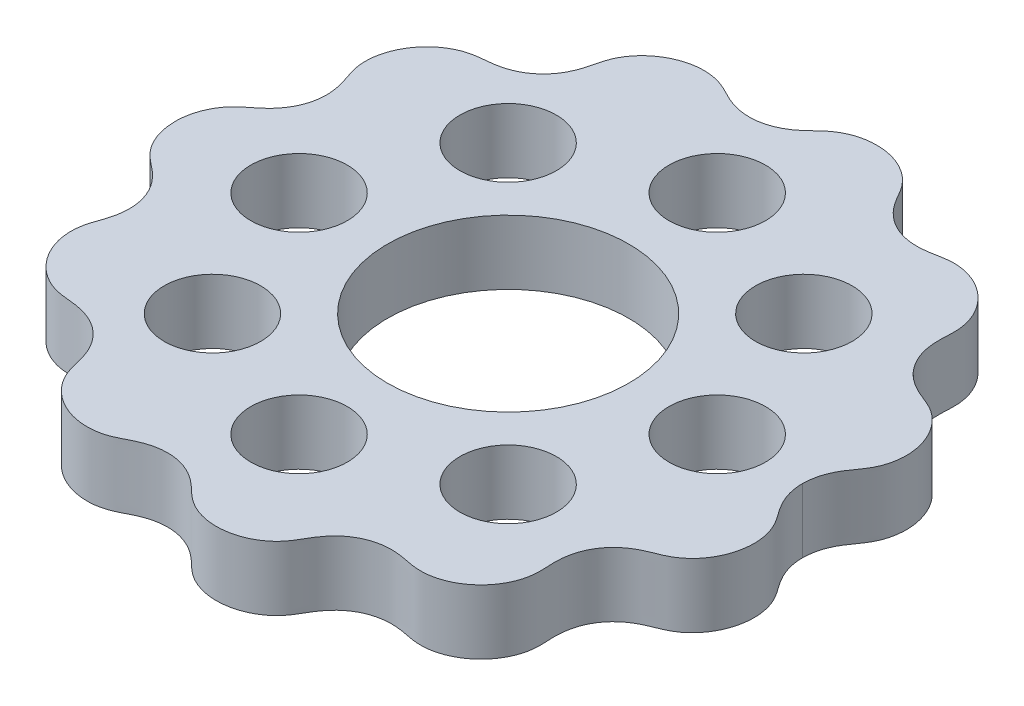
SolidWorks part; units mm, degrees
ref_plane "Front Plane" through (0, 0, 0) normal (0, 0, 1) x (1, 0, 0)
ref_plane "Top Plane" through (0, 0, 0) normal (0, 1, 0) x (1, 0, 0)
ref_plane "Right Plane" through (0, 0, 0) normal (1, 0, 0) x (0, 0, -1)
sketch "Sketch3" plane through (0, 0, 0) normal (0, 1, 0) x (1, 0, 0)
  line L0 (-30.6051, 0) -> (34.7487, 0) construction
  line L1 (0, 0) -> (0, 29.2445) construction
  spline S0 degree 4 poles (11.6189, 16.5432) (11.8178, 16.5149) (12.2108, 16.4276) (12.9492, 16.1436) (13.746, 15.5555) (14.3617, 14.7904) (14.7236, 13.9501) (14.8612, 13.2918) (14.865, 12.6715) (14.8197, 12.1053) (14.83, 11.5815) (14.8956, 11.1092) (15.007, 10.6932) (15.1452, 10.3349) (15.3154, 10.0076) (15.511, 9.7126) (15.7246, 9.4508) (15.9525, 9.2201) (16.1975, 9.0122) (16.4653, 8.8248) (16.7029, 8.6844) (16.9312, 8.5703) (17.1246, 8.4809) (17.3959, 8.3693) (17.5318, 8.3168) (17.8356, 8.1923) (18.031, 8.0988) (18.2545, 7.9769) (18.4535, 7.8462) (18.6983, 7.6613) (18.9517, 7.427) (19.209, 7.1339) (19.4525, 6.7789) (19.6486, 6.416) (19.8087, 6.0265) (19.9293, 5.6134) (20.0053, 5.1807) (20.0322, 4.7331) (20.0052, 4.2575) (19.9105, 3.7618) (19.734, 3.2584) (19.4598, 2.7684) (19.1286, 2.3294) (18.8254, 1.8814) (18.5806, 1.4078) (18.4064, 0.9137) (18.2839, 0.2821) (18.2883, -0.4839) (18.4665, -1.1796) (18.761, -1.77) (19.0269, -2.1778) (19.2109, -2.4357) (19.3957, -2.6929) (19.5656, -2.9607) (19.7479, -3.3127) (19.9386, -3.8341) (20.0574, -4.5402) (20.0084, -5.4053) (19.7399, -6.2999) (19.3164, -7.0355) (18.8045, -7.5977) (18.2523, -8.0019) (17.7028, -8.2583) (17.046, -8.4959) (16.3381, -8.8646) (15.6539, -9.4505) (15.1112, -10.2886) (14.8757, -11.08) (14.8227, -11.7251) (14.8331, -12.2747) (14.8653, -12.7277) (14.8627, -13.2601) (14.7284, -13.933) (14.4312, -14.6359) (13.9398, -15.3293) (13.2393, -15.9473) (12.4754, -16.3531) (11.7867, -16.5408) (11.2352, -16.5867) (10.8405, -16.5694) (10.5271, -16.5278) (10.2173, -16.4674) (9.9074, -16.4068) (9.4278, -16.3326) (8.7706, -16.3058) (7.9522, -16.4462) (7.0575, -16.8866) (6.3973, -17.4923) (5.9486, -18.142) (5.6247, -18.753) (5.2858, -19.2492) (4.8047, -19.7257) (4.176, -20.14) (3.4024, -20.4398) (2.5087, -20.57) (1.6927, -20.5039) (0.9916, -20.296) (0.4189, -19.998) (-0.0273, -19.6575) (-0.4146, -19.2674) (-0.8145, -18.9035) (-1.248, -18.5935) (-1.7119, -18.3505) (-2.3194, -18.1387) (-3.0782, -18.0333) (-3.7924, -18.11) (-4.4191, -18.3171) (-4.861, -18.5221) (-5.1425, -18.6675) (-5.4235, -18.8139) (-5.7127, -18.9442) (-6.0871, -19.0749) (-6.6306, -19.1899) (-7.3467, -19.2073) (-8.1962, -19.036) (-9.0436, -18.6432) (-9.7116, -18.1198) (-10.1953, -17.5335) (-10.5171, -16.93) (-10.6931, -16.3498) (-10.8346, -15.6663) (-11.0981, -14.9129) (-11.5802, -14.1521) (-12.3327, -13.4935) (-13.154, -13.1159) (-13.9425, -12.956) (-14.6452, -12.9123) (-15.2508, -12.8226) (-15.8975, -12.5902) (-16.5474, -12.1958) (-17.16, -11.6117) (-17.6691, -10.8344) (-17.9616, -10.0228) (-18.0497, -9.3149) (-18.017, -8.7626) (-17.9441, -8.3745) (-17.8585, -8.0703) (-17.7548, -7.7723) (-17.6507, -7.4743) (-17.5088, -7.0104) (-17.3883, -6.3641) (-17.4099, -5.5341) (-17.7175, -4.5856) (-18.2225, -3.8453) (-18.8015, -3.308) (-19.3605, -2.9003) (-19.8039, -2.4944) (-20.2076, -1.9504) (-20.5288, -1.269) (-20.7158, -0.4605) (-20.7178, 0.4427) (-20.5366, 1.2408) (-20.2316, 1.9051) (-19.8556, 2.4296) (-19.4556, 2.8229) (-19.0146, 3.1507) (-18.5974, 3.4944) (-18.2288, 3.8789) (-17.9219, 4.3031) (-17.6253, 4.8739) (-17.4121, 5.6098) (-17.3857, 6.3278) (-17.501, 6.9779) (-17.6409, 7.4447) (-17.7447, 7.7443) (-17.8497, 8.0433) (-17.9378, 8.3482) (-18.0142, 8.7375) (-18.051, 9.292) (-17.9667, 10.0036) (-17.6765, 10.8204) (-17.1675, 11.6035) (-16.5546, 12.1903) (-15.906, 12.5859) (-15.2632, 12.8188) (-14.6642, 12.9109) (-13.9676, 12.9536) (-13.185, 13.1065) (-12.3627, 13.4746) (-11.6037, 14.1249) (-11.1111, 14.8837) (-10.8676, 15.5695) (-10.7424, 16.1072) (-10.6331, 16.5515) (-10.4857, 16.9859) (-10.2015, 17.5258) (-9.7176, 18.1133) (-9.0531, 18.6371) (-8.2109, 19.0306) (-7.3665, 19.205) (-6.6533, 19.1918) (-6.1116, 19.0813) (-5.7378, 18.9541) (-5.4489, 18.8264) (-5.1688, 18.6814) (-4.8888, 18.536) (-4.4501, 18.3294) (-3.8279, 18.1177) (-3.0036, 18.0202) (-2.0208, 18.1887) (-1.2156, 18.5825) (-0.6007, 19.0789) (-0.1174, 19.5743) (0.3474, 19.956) (0.9434, 20.2787) (1.6637, 20.5001) (2.4907, 20.5705) (3.385, 20.4443) (4.1492, 20.1518) (4.7633, 19.7558) (5.229, 19.3095) (5.5616, 18.8581) (5.8234, 18.3752) (6.1038, 17.9134) (6.4315, 17.4937) (6.8071, 17.1293) (7.2217, 16.8315) (7.6634, 16.6034) (8.1203, 16.4444) (8.5815, 16.3511) (9.0507, 16.319) (9.4616, 16.3412) (9.8101, 16.3903) (10.0986, 16.4439) (10.3282, 16.4895) (10.5311, 16.526) (10.7049, 16.5505) (10.8484, 16.5653) (10.9716, 16.5733) (11.0921, 16.577) (11.1677, 16.5774) (11.2594, 16.5751) (11.3499, 16.5709) (11.4367, 16.5647) (11.5194, 16.5564) (11.6217, 16.5435) (11.7453, 16.524) (11.889, 16.4956) (12.0913, 16.4453) (12.3305, 16.3702) (12.602, 16.2618) (12.9005, 16.1114) (13.1849, 15.9359) (13.4773, 15.7195) (13.7698, 15.4569) (14.0541, 15.1433) (14.3167, 14.7752) (14.5534, 14.3454) (14.7409, 13.8521) (14.8591, 13.2967) (14.8673, 12.6928) (14.8104, 11.9996) (14.8464, 11.2056) (15.0918, 10.3263) (15.5701, 9.57) (16.1316, 9.0373) (16.5735, 8.7549) (16.8048, 8.6327) (16.9225, 8.5759) knots 0 0 0 0 0 0.005432 0.010864 0.021228 0.026411 0.031594 0.035438 0.039283 0.043127 0.046971 0.049563 0.052156 0.054748 0.057341 0.059524 0.061707 0.06389 0.066073 0.068256 0.070439 0.07153 0.072622 0.074805 0.076449 0.078093 0.079737 0.081382 0.083026 0.08467 0.087958 0.090741 0.093524 0.096307 0.09909 0.102115 0.105141 0.108166 0.111192 0.114971 0.11875 0.122529 0.126307 0.129839 0.133371 0.136903 0.140435 0.147176 0.153918 0.15606 0.158202 0.160344 0.162486 0.164628 0.16677 0.171054 0.177448 0.183843 0.189974 0.196106 0.20019 0.204275 0.20836 0.212445 0.219092 0.225739 0.23241 0.239081 0.24113 0.243178 0.247276 0.251373 0.255471 0.261622 0.267773 0.274148 0.280522 0.284792 0.286927 0.289062 0.291197 0.293332 0.295467 0.297602 0.304323 0.311044 0.317625 0.324205 0.32825 0.332295 0.33634 0.340384 0.346455 0.352526 0.358575 0.364624 0.368401 0.372178 0.375955 0.379732 0.383263 0.386793 0.390324 0.393854 0.400599 0.407343 0.409486 0.411628 0.413771 0.415914 0.418057 0.4202 0.424485 0.430883 0.43728 0.443409 0.449537 0.453621 0.457704 0.461787 0.465871 0.472515 0.479159 0.485846 0.492533 0.496656 0.50078 0.504903 0.509026 0.515118 0.52121 0.527582 0.533954 0.538222 0.540357 0.542491 0.544625 0.546759 0.548893 0.551027 0.557745 0.564464 0.571047 0.57763 0.581676 0.585723 0.589769 0.593816 0.59989 0.605963 0.612009 0.618055 0.621831 0.625606 0.629382 0.633157 0.636687 0.640216 0.643745 0.647274 0.654021 0.660768 0.662911 0.665055 0.667199 0.669342 0.671486 0.67363 0.677917 0.684317 0.690717 0.696843 0.702969 0.707051 0.711133 0.715214 0.719296 0.725937 0.732578 0.739268 0.745958 0.750083 0.752145 0.754208 0.758333 0.762458 0.768552 0.774647 0.781016 0.787386 0.791652 0.793786 0.795919 0.798052 0.800186 0.802319 0.804452 0.811168 0.817883 0.824469 0.831054 0.835103 0.839151 0.843199 0.847248 0.853324 0.8594 0.865444 0.871487 0.875261 0.879035 0.882809 0.886583 0.89011 0.893638 0.897166 0.900694 0.903866 0.907039 0.910211 0.913384 0.916556 0.918143 0.919729 0.921315 0.922901 0.923694 0.924488 0.925281 0.926074 0.926638 0.927203 0.927767 0.928331 0.928896 0.92946 0.930589 0.931717 0.932846 0.935103 0.937361 0.939618 0.941875 0.944133 0.947186 0.95024 0.953293 0.956347 0.960414 0.964482 0.968549 0.972617 0.979237 0.985858 0.992929 0.996465 1 1 1 1 1 construction
  spline S1 degree 4 poles (18.3, 0) (18.3, -0.215) (18.3388, -0.6792) (18.4818, -1.2103) (18.761, -1.77) (19.0269, -2.1778) (19.2109, -2.4357) (19.3957, -2.6929) (19.5656, -2.9607) (19.7479, -3.3127) (19.9386, -3.8341) (20.0574, -4.5402) (20.0084, -5.4053) (19.7399, -6.2999) (19.3164, -7.0355) (18.8045, -7.5977) (18.2523, -8.0019) (17.7028, -8.2583) (17.046, -8.4959) (16.3381, -8.8646) (15.6539, -9.4505) (15.1112, -10.2886) (14.8757, -11.08) (14.8227, -11.7251) (14.8331, -12.2747) (14.8653, -12.7277) (14.8627, -13.2601) (14.7284, -13.933) (14.4312, -14.6359) (13.9398, -15.3293) (13.2393, -15.9473) (12.4754, -16.3531) (11.7867, -16.5408) (11.2352, -16.5867) (10.8405, -16.5694) (10.5271, -16.5278) (10.2173, -16.4674) (9.9074, -16.4068) (9.4278, -16.3326) (8.7706, -16.3058) (7.9522, -16.4462) (7.0575, -16.8866) (6.3973, -17.4923) (5.9486, -18.142) (5.6247, -18.753) (5.2858, -19.2492) (4.8047, -19.7257) (4.176, -20.14) (3.4024, -20.4398) (2.5087, -20.57) (1.6927, -20.5039) (0.9916, -20.296) (0.4189, -19.998) (-0.0273, -19.6575) (-0.4146, -19.2674) (-0.8145, -18.9035) (-1.248, -18.5935) (-1.7119, -18.3505) (-2.3194, -18.1387) (-3.0782, -18.0333) (-3.7924, -18.11) (-4.4191, -18.3171) (-4.861, -18.5221) (-5.1425, -18.6675) (-5.4235, -18.8139) (-5.7127, -18.9442) (-6.0871, -19.0749) (-6.6306, -19.1899) (-7.3467, -19.2073) (-8.1962, -19.036) (-9.0436, -18.6432) (-9.7116, -18.1198) (-10.1953, -17.5335) (-10.5171, -16.93) (-10.6931, -16.3498) (-10.8346, -15.6663) (-11.0981, -14.9129) (-11.5802, -14.1521) (-12.3327, -13.4935) (-13.154, -13.1159) (-13.9425, -12.956) (-14.6452, -12.9123) (-15.2508, -12.8226) (-15.8975, -12.5902) (-16.5474, -12.1958) (-17.16, -11.6117) (-17.6691, -10.8344) (-17.9616, -10.0228) (-18.0497, -9.3149) (-18.017, -8.7626) (-17.9441, -8.3745) (-17.8585, -8.0703) (-17.7548, -7.7723) (-17.6507, -7.4743) (-17.5088, -7.0104) (-17.3883, -6.3641) (-17.4099, -5.5341) (-17.7175, -4.5856) (-18.2225, -3.8453) (-18.8015, -3.308) (-19.3605, -2.9003) (-19.8039, -2.4944) (-20.2076, -1.9504) (-20.5295, -1.2674) (-20.6657, -0.677) (-20.7, -0.2262) (-20.7, 0) knots 0.14136 0.14136 0.14136 0.14136 0.14136 0.147176 0.153918 0.15606 0.158202 0.160344 0.162486 0.164628 0.16677 0.171054 0.177448 0.183843 0.189974 0.196106 0.20019 0.204275 0.20836 0.212445 0.219092 0.225739 0.23241 0.239081 0.24113 0.243178 0.247276 0.251373 0.255471 0.261622 0.267773 0.274148 0.280522 0.284792 0.286927 0.289062 0.291197 0.293332 0.295467 0.297602 0.304323 0.311044 0.317625 0.324205 0.32825 0.332295 0.33634 0.340384 0.346455 0.352526 0.358575 0.364624 0.368401 0.372178 0.375955 0.379732 0.383263 0.386793 0.390324 0.393854 0.400599 0.407343 0.409486 0.411628 0.413771 0.415914 0.418057 0.4202 0.424485 0.430883 0.43728 0.443409 0.449537 0.453621 0.457704 0.461787 0.465871 0.472515 0.479159 0.485846 0.492533 0.496656 0.50078 0.504903 0.509026 0.515118 0.52121 0.527582 0.533954 0.538222 0.540357 0.542491 0.544625 0.546759 0.548893 0.551027 0.557745 0.564464 0.571047 0.57763 0.581676 0.585723 0.589769 0.593816 0.59989 0.60601 0.60601 0.60601 0.60601 0.60601
  spline S2 degree 4 poles (18.3, 0) (18.3, 0.215) (18.3388, 0.6792) (18.4818, 1.2103) (18.761, 1.77) (19.0269, 2.1778) (19.2109, 2.4357) (19.3957, 2.6929) (19.5656, 2.9607) (19.7479, 3.3127) (19.9386, 3.8341) (20.0574, 4.5402) (20.0084, 5.4053) (19.7399, 6.2999) (19.3164, 7.0355) (18.8045, 7.5977) (18.2523, 8.0019) (17.7028, 8.2583) (17.046, 8.4959) (16.3381, 8.8646) (15.6539, 9.4505) (15.1112, 10.2886) (14.8757, 11.08) (14.8227, 11.7251) (14.8331, 12.2747) (14.8653, 12.7277) (14.8627, 13.2601) (14.7284, 13.933) (14.4312, 14.6359) (13.9398, 15.3293) (13.2393, 15.9473) (12.4754, 16.3531) (11.7867, 16.5408) (11.2352, 16.5867) (10.8405, 16.5694) (10.5271, 16.5278) (10.2173, 16.4674) (9.9074, 16.4068) (9.4278, 16.3326) (8.7706, 16.3058) (7.9522, 16.4462) (7.0575, 16.8866) (6.3973, 17.4923) (5.9486, 18.142) (5.6247, 18.753) (5.2858, 19.2492) (4.8047, 19.7257) (4.176, 20.14) (3.4024, 20.4398) (2.5087, 20.57) (1.6927, 20.5039) (0.9916, 20.296) (0.4189, 19.998) (-0.0273, 19.6575) (-0.4146, 19.2674) (-0.8145, 18.9035) (-1.248, 18.5935) (-1.7119, 18.3505) (-2.3194, 18.1387) (-3.0782, 18.0333) (-3.7924, 18.11) (-4.4191, 18.3171) (-4.861, 18.5221) (-5.1425, 18.6675) (-5.4235, 18.8139) (-5.7127, 18.9442) (-6.0871, 19.0749) (-6.6306, 19.1899) (-7.3467, 19.2073) (-8.1962, 19.036) (-9.0436, 18.6432) (-9.7116, 18.1198) (-10.1953, 17.5335) (-10.5171, 16.93) (-10.6931, 16.3498) (-10.8346, 15.6663) (-11.0981, 14.9129) (-11.5802, 14.1521) (-12.3327, 13.4935) (-13.154, 13.1159) (-13.9425, 12.956) (-14.6452, 12.9123) (-15.2508, 12.8226) (-15.8975, 12.5902) (-16.5474, 12.1958) (-17.16, 11.6117) (-17.6691, 10.8344) (-17.9616, 10.0228) (-18.0497, 9.3149) (-18.017, 8.7626) (-17.9441, 8.3745) (-17.8585, 8.0703) (-17.7548, 7.7723) (-17.6507, 7.4743) (-17.5088, 7.0104) (-17.3883, 6.3641) (-17.4099, 5.5341) (-17.7175, 4.5856) (-18.2225, 3.8453) (-18.8015, 3.308) (-19.3605, 2.9003) (-19.8039, 2.4944) (-20.2076, 1.9504) (-20.5295, 1.2674) (-20.6657, 0.677) (-20.7, 0.2262) (-20.7, 0) knots 0.14136 0.14136 0.14136 0.14136 0.14136 0.147176 0.153918 0.15606 0.158202 0.160344 0.162486 0.164628 0.16677 0.171054 0.177448 0.183843 0.189974 0.196106 0.20019 0.204275 0.20836 0.212445 0.219092 0.225739 0.23241 0.239081 0.24113 0.243178 0.247276 0.251373 0.255471 0.261622 0.267773 0.274148 0.280522 0.284792 0.286927 0.289062 0.291197 0.293332 0.295467 0.297602 0.304323 0.311044 0.317625 0.324205 0.32825 0.332295 0.33634 0.340384 0.346455 0.352526 0.358575 0.364624 0.368401 0.372178 0.375955 0.379732 0.383263 0.386793 0.390324 0.393854 0.400599 0.407343 0.409486 0.411628 0.413771 0.415914 0.418057 0.4202 0.424485 0.430883 0.43728 0.443409 0.449537 0.453621 0.457704 0.461787 0.465871 0.472515 0.479159 0.485846 0.492533 0.496656 0.50078 0.504903 0.509026 0.515118 0.52121 0.527582 0.533954 0.538222 0.540357 0.542491 0.544625 0.546759 0.548893 0.551027 0.557745 0.564464 0.571047 0.57763 0.581676 0.585723 0.589769 0.593816 0.59989 0.60601 0.60601 0.60601 0.60601 0.60601
sketch "Sketch4" plane through (0, 0, 0) normal (0, 1, 0) x (1, 0, 0)
  line L0 (-200030.6051, 0) -> (200034.7487, 0) construction
  circle A0 centre (0, 0) radius 7.5
  circle A1 centre (0, 0) radius 13 construction
  circle A2 centre (-13, 0) radius 3
  circle A3 centre (-9.1924, 9.1924) radius 3
  circle A4 centre (0, 13) radius 3
  circle A5 centre (9.1924, 9.1924) radius 3
  circle A6 centre (13, 0) radius 3
  circle A7 centre (9.1924, -9.1924) radius 3
  circle A8 centre (0, -13) radius 3
  circle A9 centre (-9.1924, -9.1924) radius 3
  point P8 (0, 0)
  point P9 (15.4334, -4.2634)
  point P24 (0, 0)
  point P25 (0, 0)
  dimension "D2" = 15
  dimension "D1" = 6
  dimension "D3" = 26
  dimension "D4" = 8
sketch "Sketch5" plane through (0, 0, 0) normal (0, 1, 0) x (1, 0, 0)
  circle A0 centre (0, 0) radius 7.5 construction
  circle A1 centre (-9.1924, -9.1924) radius 3 construction
  circle A2 centre (0, -13) radius 3 construction
  circle A3 centre (9.1924, -9.1924) radius 3 construction
  circle A4 centre (13, 0) radius 3 construction
  circle A5 centre (9.1924, 9.1924) radius 3 construction
  circle A6 centre (0, 13) radius 3 construction
  circle A7 centre (-9.1924, 9.1924) radius 3 construction
  circle A8 centre (-13, 0) radius 3 construction
  circle A9 centre (0, 0) radius 7.5
  circle A10 centre (-9.1924, -9.1924) radius 3
  circle A11 centre (0, -13) radius 3
  circle A12 centre (9.1924, -9.1924) radius 3
  circle A13 centre (13, 0) radius 3
  circle A14 centre (9.1924, 9.1924) radius 3
  circle A15 centre (0, 13) radius 3
  circle A16 centre (-9.1924, 9.1924) radius 3
  circle A17 centre (-13, 0) radius 3
  spline S0 degree 4 poles (-2748.9777, 1148.302) (182.2582, 110.6656) (41.0051, -28.4684) (14.4609, -6.8501) (18.761, 1.77) (19.0269, 2.1778) (19.2109, 2.4357) (19.3957, 2.6929) (19.5656, 2.9607) (19.7479, 3.3127) (19.9386, 3.8341) (20.0574, 4.5402) (20.0084, 5.4053) (19.7399, 6.2999) (19.3164, 7.0355) (18.8045, 7.5977) (18.2523, 8.0019) (17.7028, 8.2583) (17.046, 8.4959) (16.3381, 8.8646) (15.6539, 9.4505) (15.1112, 10.2886) (14.8757, 11.08) (14.8227, 11.7251) (14.8331, 12.2747) (14.8653, 12.7277) (14.8627, 13.2601) (14.7284, 13.933) (14.4312, 14.6359) (13.9398, 15.3293) (13.2393, 15.9473) (12.4754, 16.3531) (11.7867, 16.5408) (11.2352, 16.5867) (10.8405, 16.5694) (10.5271, 16.5278) (10.2173, 16.4674) (9.9074, 16.4068) (9.4278, 16.3326) (8.7706, 16.3058) (7.9522, 16.4462) (7.0575, 16.8866) (6.3973, 17.4923) (5.9486, 18.142) (5.6247, 18.753) (5.2858, 19.2492) (4.8047, 19.7257) (4.176, 20.14) (3.4024, 20.4398) (2.5087, 20.57) (1.6927, 20.5039) (0.9916, 20.296) (0.4189, 19.998) (-0.0273, 19.6575) (-0.4146, 19.2674) (-0.8145, 18.9035) (-1.248, 18.5935) (-1.7119, 18.3505) (-2.3194, 18.1387) (-3.0782, 18.0333) (-3.7924, 18.11) (-4.4191, 18.3171) (-4.861, 18.5221) (-5.1425, 18.6675) (-5.4235, 18.8139) (-5.7127, 18.9442) (-6.0871, 19.0749) (-6.6306, 19.1899) (-7.3467, 19.2073) (-8.1962, 19.036) (-9.0436, 18.6432) (-9.7116, 18.1198) (-10.1953, 17.5335) (-10.5171, 16.93) (-10.6931, 16.3498) (-10.8346, 15.6663) (-11.0981, 14.9129) (-11.5802, 14.1521) (-12.3327, 13.4935) (-13.154, 13.1159) (-13.9425, 12.956) (-14.6452, 12.9123) (-15.2508, 12.8226) (-15.8975, 12.5902) (-16.5474, 12.1958) (-17.16, 11.6117) (-17.6691, 10.8344) (-17.9616, 10.0228) (-18.0497, 9.3149) (-18.017, 8.7626) (-17.9441, 8.3745) (-17.8585, 8.0703) (-17.7548, 7.7723) (-17.6507, 7.4743) (-17.5088, 7.0104) (-17.3883, 6.3641) (-17.4099, 5.5341) (-17.7175, 4.5856) (-18.2225, 3.8453) (-18.8015, 3.308) (-19.3605, 2.9003) (-19.8039, 2.4944) (-20.2076, 1.9504) (-26.3458, -11.073) (35.0631, -48.2959) (149.4782, 410.1171) (1411.5598, -2615.9413) knots -0.101211 -0.101211 -0.101211 -0.101211 -0.101211 0.147176 0.153918 0.15606 0.158202 0.160344 0.162486 0.164628 0.16677 0.171054 0.177448 0.183843 0.189974 0.196106 0.20019 0.204275 0.20836 0.212445 0.219092 0.225739 0.23241 0.239081 0.24113 0.243178 0.247276 0.251373 0.255471 0.261622 0.267773 0.274148 0.280522 0.284792 0.286927 0.289062 0.291197 0.293332 0.295467 0.297602 0.304323 0.311044 0.317625 0.324205 0.32825 0.332295 0.33634 0.340384 0.346455 0.352526 0.358575 0.364624 0.368401 0.372178 0.375955 0.379732 0.383263 0.386793 0.390324 0.393854 0.400599 0.407343 0.409486 0.411628 0.413771 0.415914 0.418057 0.4202 0.424485 0.430883 0.43728 0.443409 0.449537 0.453621 0.457704 0.461787 0.465871 0.472515 0.479159 0.485846 0.492533 0.496656 0.50078 0.504903 0.509026 0.515118 0.52121 0.527582 0.533954 0.538222 0.540357 0.542491 0.544625 0.546759 0.548893 0.551027 0.557745 0.564464 0.571047 0.57763 0.581676 0.585723 0.589769 0.593816 0.59989 0.972598 0.972598 0.972598 0.972598 0.972598 only from (18.3, 0) to (-20.7, 0) construction
  spline S1 degree 4 poles (-2748.9777, -1148.302) (182.2582, -110.6656) (41.0051, 28.4684) (14.4609, 6.8501) (18.761, -1.77) (19.0269, -2.1778) (19.2109, -2.4357) (19.3957, -2.6929) (19.5656, -2.9607) (19.7479, -3.3127) (19.9386, -3.8341) (20.0574, -4.5402) (20.0084, -5.4053) (19.7399, -6.2999) (19.3164, -7.0355) (18.8045, -7.5977) (18.2523, -8.0019) (17.7028, -8.2583) (17.046, -8.4959) (16.3381, -8.8646) (15.6539, -9.4505) (15.1112, -10.2886) (14.8757, -11.08) (14.8227, -11.7251) (14.8331, -12.2747) (14.8653, -12.7277) (14.8627, -13.2601) (14.7284, -13.933) (14.4312, -14.6359) (13.9398, -15.3293) (13.2393, -15.9473) (12.4754, -16.3531) (11.7867, -16.5408) (11.2352, -16.5867) (10.8405, -16.5694) (10.5271, -16.5278) (10.2173, -16.4674) (9.9074, -16.4068) (9.4278, -16.3326) (8.7706, -16.3058) (7.9522, -16.4462) (7.0575, -16.8866) (6.3973, -17.4923) (5.9486, -18.142) (5.6247, -18.753) (5.2858, -19.2492) (4.8047, -19.7257) (4.176, -20.14) (3.4024, -20.4398) (2.5087, -20.57) (1.6927, -20.5039) (0.9916, -20.296) (0.4189, -19.998) (-0.0273, -19.6575) (-0.4146, -19.2674) (-0.8145, -18.9035) (-1.248, -18.5935) (-1.7119, -18.3505) (-2.3194, -18.1387) (-3.0782, -18.0333) (-3.7924, -18.11) (-4.4191, -18.3171) (-4.861, -18.5221) (-5.1425, -18.6675) (-5.4235, -18.8139) (-5.7127, -18.9442) (-6.0871, -19.0749) (-6.6306, -19.1899) (-7.3467, -19.2073) (-8.1962, -19.036) (-9.0436, -18.6432) (-9.7116, -18.1198) (-10.1953, -17.5335) (-10.5171, -16.93) (-10.6931, -16.3498) (-10.8346, -15.6663) (-11.0981, -14.9129) (-11.5802, -14.1521) (-12.3327, -13.4935) (-13.154, -13.1159) (-13.9425, -12.956) (-14.6452, -12.9123) (-15.2508, -12.8226) (-15.8975, -12.5902) (-16.5474, -12.1958) (-17.16, -11.6117) (-17.6691, -10.8344) (-17.9616, -10.0228) (-18.0497, -9.3149) (-18.017, -8.7626) (-17.9441, -8.3745) (-17.8585, -8.0703) (-17.7548, -7.7723) (-17.6507, -7.4743) (-17.5088, -7.0104) (-17.3883, -6.3641) (-17.4099, -5.5341) (-17.7175, -4.5856) (-18.2225, -3.8453) (-18.8015, -3.308) (-19.3605, -2.9003) (-19.8039, -2.4944) (-20.2076, -1.9504) (-26.3458, 11.073) (35.0631, 48.2959) (149.4782, -410.1171) (1411.56, 2615.9413) knots -0.101211 -0.101211 -0.101211 -0.101211 -0.101211 0.147176 0.153918 0.15606 0.158202 0.160344 0.162486 0.164628 0.16677 0.171054 0.177448 0.183843 0.189974 0.196106 0.20019 0.204275 0.20836 0.212445 0.219092 0.225739 0.23241 0.239081 0.24113 0.243178 0.247276 0.251373 0.255471 0.261622 0.267773 0.274148 0.280522 0.284792 0.286927 0.289062 0.291197 0.293332 0.295467 0.297602 0.304323 0.311044 0.317625 0.324205 0.32825 0.332295 0.33634 0.340384 0.346455 0.352526 0.358575 0.364624 0.368401 0.372178 0.375955 0.379732 0.383263 0.386793 0.390324 0.393854 0.400599 0.407343 0.409486 0.411628 0.413771 0.415914 0.418057 0.4202 0.424485 0.430883 0.43728 0.443409 0.449537 0.453621 0.457704 0.461787 0.465871 0.472515 0.479159 0.485846 0.492533 0.496656 0.50078 0.504903 0.509026 0.515118 0.52121 0.527582 0.533954 0.538222 0.540357 0.542491 0.544625 0.546759 0.548893 0.551027 0.557745 0.564464 0.571047 0.57763 0.581676 0.585723 0.589769 0.593816 0.59989 0.972598 0.972598 0.972598 0.972598 0.972598 only from (18.3, 0) to (-20.7, 0) construction
  spline S2 degree 4 poles (18.3, 0) (18.3, 0.215) (18.3388, 0.6792) (18.4818, 1.2103) (18.761, 1.77) (19.0269, 2.1778) (19.2109, 2.4357) (19.3957, 2.6929) (19.5656, 2.9607) (19.7479, 3.3127) (19.9386, 3.8341) (20.0574, 4.5402) (20.0084, 5.4053) (19.7399, 6.2999) (19.3164, 7.0355) (18.8045, 7.5977) (18.2523, 8.0019) (17.7028, 8.2583) (17.046, 8.4959) (16.3381, 8.8646) (15.6539, 9.4505) (15.1112, 10.2886) (14.8757, 11.08) (14.8227, 11.7251) (14.8331, 12.2747) (14.8653, 12.7277) (14.8627, 13.2601) (14.7284, 13.933) (14.4312, 14.6359) (13.9398, 15.3293) (13.2393, 15.9473) (12.4754, 16.3531) (11.7867, 16.5408) (11.2352, 16.5867) (10.8405, 16.5694) (10.5271, 16.5278) (10.2173, 16.4674) (9.9074, 16.4068) (9.4278, 16.3326) (8.7706, 16.3058) (7.9522, 16.4462) (7.0575, 16.8866) (6.3973, 17.4923) (5.9486, 18.142) (5.6247, 18.753) (5.2858, 19.2492) (4.8047, 19.7257) (4.176, 20.14) (3.4024, 20.4398) (2.5087, 20.57) (1.6927, 20.5039) (0.9916, 20.296) (0.4189, 19.998) (-0.0273, 19.6575) (-0.4146, 19.2674) (-0.8145, 18.9035) (-1.248, 18.5935) (-1.7119, 18.3505) (-2.3194, 18.1387) (-3.0782, 18.0333) (-3.7924, 18.11) (-4.4191, 18.3171) (-4.861, 18.5221) (-5.1425, 18.6675) (-5.4235, 18.8139) (-5.7127, 18.9442) (-6.0871, 19.0749) (-6.6306, 19.1899) (-7.3467, 19.2073) (-8.1962, 19.036) (-9.0436, 18.6432) (-9.7116, 18.1198) (-10.1953, 17.5335) (-10.5171, 16.93) (-10.6931, 16.3498) (-10.8346, 15.6663) (-11.0981, 14.9129) (-11.5802, 14.1521) (-12.3327, 13.4935) (-13.154, 13.1159) (-13.9425, 12.956) (-14.6452, 12.9123) (-15.2508, 12.8226) (-15.8975, 12.5902) (-16.5474, 12.1958) (-17.16, 11.6117) (-17.6691, 10.8344) (-17.9616, 10.0228) (-18.0497, 9.3149) (-18.017, 8.7626) (-17.9441, 8.3745) (-17.8585, 8.0703) (-17.7548, 7.7723) (-17.6507, 7.4743) (-17.5088, 7.0104) (-17.3883, 6.3641) (-17.4099, 5.5341) (-17.7175, 4.5856) (-18.2225, 3.8453) (-18.8015, 3.308) (-19.3605, 2.9003) (-19.8039, 2.4944) (-20.2076, 1.9504) (-20.5295, 1.2674) (-20.6657, 0.677) (-20.7, 0.2262) (-20.7, 0) knots 0.14136 0.14136 0.14136 0.14136 0.14136 0.147176 0.153918 0.15606 0.158202 0.160344 0.162486 0.164628 0.16677 0.171054 0.177448 0.183843 0.189974 0.196106 0.20019 0.204275 0.20836 0.212445 0.219092 0.225739 0.23241 0.239081 0.24113 0.243178 0.247276 0.251373 0.255471 0.261622 0.267773 0.274148 0.280522 0.284792 0.286927 0.289062 0.291197 0.293332 0.295467 0.297602 0.304323 0.311044 0.317625 0.324205 0.32825 0.332295 0.33634 0.340384 0.346455 0.352526 0.358575 0.364624 0.368401 0.372178 0.375955 0.379732 0.383263 0.386793 0.390324 0.393854 0.400599 0.407343 0.409486 0.411628 0.413771 0.415914 0.418057 0.4202 0.424485 0.430883 0.43728 0.443409 0.449537 0.453621 0.457704 0.461787 0.465871 0.472515 0.479159 0.485846 0.492533 0.496656 0.50078 0.504903 0.509026 0.515118 0.52121 0.527582 0.533954 0.538222 0.540357 0.542491 0.544625 0.546759 0.548893 0.551027 0.557745 0.564464 0.571047 0.57763 0.581676 0.585723 0.589769 0.593816 0.59989 0.60601 0.60601 0.60601 0.60601 0.60601
  spline S3 degree 4 poles (18.3, 0) (18.3, -0.215) (18.3388, -0.6792) (18.4818, -1.2103) (18.761, -1.77) (19.0269, -2.1778) (19.2109, -2.4357) (19.3957, -2.6929) (19.5656, -2.9607) (19.7479, -3.3127) (19.9386, -3.8341) (20.0574, -4.5402) (20.0084, -5.4053) (19.7399, -6.2999) (19.3164, -7.0355) (18.8045, -7.5977) (18.2523, -8.0019) (17.7028, -8.2583) (17.046, -8.4959) (16.3381, -8.8646) (15.6539, -9.4505) (15.1112, -10.2886) (14.8757, -11.08) (14.8227, -11.7251) (14.8331, -12.2747) (14.8653, -12.7277) (14.8627, -13.2601) (14.7284, -13.933) (14.4312, -14.6359) (13.9398, -15.3293) (13.2393, -15.9473) (12.4754, -16.3531) (11.7867, -16.5408) (11.2352, -16.5867) (10.8405, -16.5694) (10.5271, -16.5278) (10.2173, -16.4674) (9.9074, -16.4068) (9.4278, -16.3326) (8.7706, -16.3058) (7.9522, -16.4462) (7.0575, -16.8866) (6.3973, -17.4923) (5.9486, -18.142) (5.6247, -18.753) (5.2858, -19.2492) (4.8047, -19.7257) (4.176, -20.14) (3.4024, -20.4398) (2.5087, -20.57) (1.6927, -20.5039) (0.9916, -20.296) (0.4189, -19.998) (-0.0273, -19.6575) (-0.4146, -19.2674) (-0.8145, -18.9035) (-1.248, -18.5935) (-1.7119, -18.3505) (-2.3194, -18.1387) (-3.0782, -18.0333) (-3.7924, -18.11) (-4.4191, -18.3171) (-4.861, -18.5221) (-5.1425, -18.6675) (-5.4235, -18.8139) (-5.7127, -18.9442) (-6.0871, -19.0749) (-6.6306, -19.1899) (-7.3467, -19.2073) (-8.1962, -19.036) (-9.0436, -18.6432) (-9.7116, -18.1198) (-10.1953, -17.5335) (-10.5171, -16.93) (-10.6931, -16.3498) (-10.8346, -15.6663) (-11.0981, -14.9129) (-11.5802, -14.1521) (-12.3327, -13.4935) (-13.154, -13.1159) (-13.9425, -12.956) (-14.6452, -12.9123) (-15.2508, -12.8226) (-15.8975, -12.5902) (-16.5474, -12.1958) (-17.16, -11.6117) (-17.6691, -10.8344) (-17.9616, -10.0228) (-18.0497, -9.3149) (-18.017, -8.7626) (-17.9441, -8.3745) (-17.8585, -8.0703) (-17.7548, -7.7723) (-17.6507, -7.4743) (-17.5088, -7.0104) (-17.3883, -6.3641) (-17.4099, -5.5341) (-17.7175, -4.5856) (-18.2225, -3.8453) (-18.8015, -3.308) (-19.3605, -2.9003) (-19.8039, -2.4944) (-20.2076, -1.9504) (-20.5295, -1.2674) (-20.6657, -0.677) (-20.7, -0.2262) (-20.7, 0) knots 0.14136 0.14136 0.14136 0.14136 0.14136 0.147176 0.153918 0.15606 0.158202 0.160344 0.162486 0.164628 0.16677 0.171054 0.177448 0.183843 0.189974 0.196106 0.20019 0.204275 0.20836 0.212445 0.219092 0.225739 0.23241 0.239081 0.24113 0.243178 0.247276 0.251373 0.255471 0.261622 0.267773 0.274148 0.280522 0.284792 0.286927 0.289062 0.291197 0.293332 0.295467 0.297602 0.304323 0.311044 0.317625 0.324205 0.32825 0.332295 0.33634 0.340384 0.346455 0.352526 0.358575 0.364624 0.368401 0.372178 0.375955 0.379732 0.383263 0.386793 0.390324 0.393854 0.400599 0.407343 0.409486 0.411628 0.413771 0.415914 0.418057 0.4202 0.424485 0.430883 0.43728 0.443409 0.449537 0.453621 0.457704 0.461787 0.465871 0.472515 0.479159 0.485846 0.492533 0.496656 0.50078 0.504903 0.509026 0.515118 0.52121 0.527582 0.533954 0.538222 0.540357 0.542491 0.544625 0.546759 0.548893 0.551027 0.557745 0.564464 0.571047 0.57763 0.581676 0.585723 0.589769 0.593816 0.59989 0.60601 0.60601 0.60601 0.60601 0.60601
extrude "Boss-Extrude1" add sketch "Sketch5" along normal blind 4
